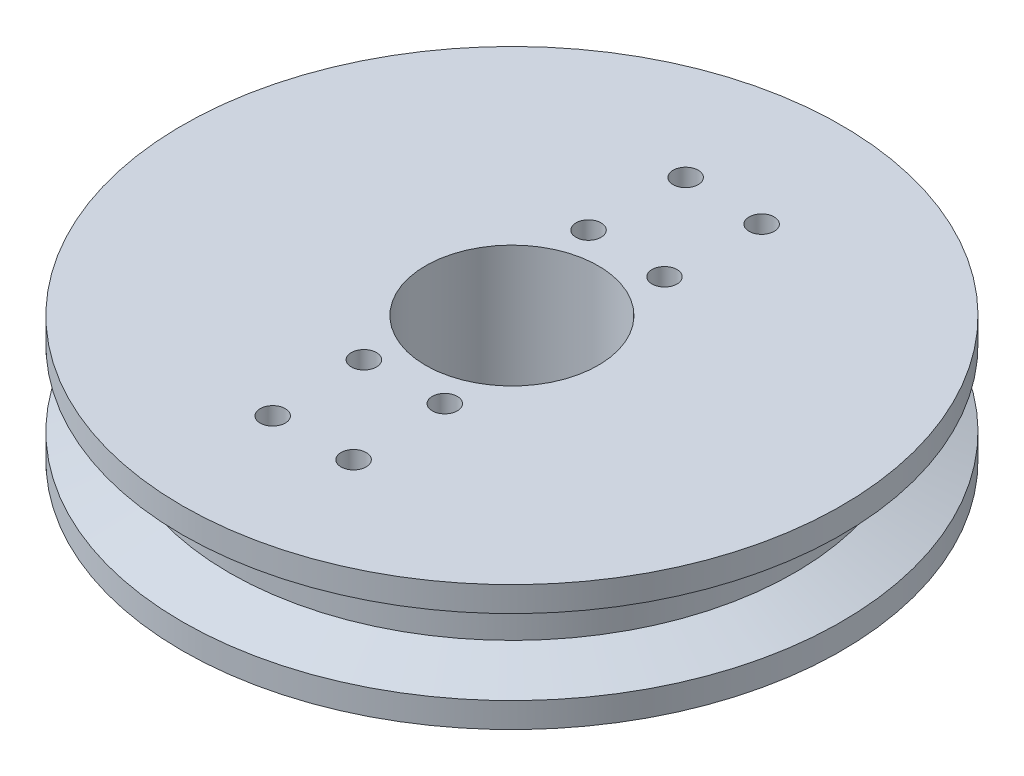
SolidWorks part; units mm, degrees
material "1060 Alloy"
ref_plane "Front Plane" through (0, 0, 0) normal (0, 0, 1) x (1, 0, 0)
ref_plane "Top Plane" through (0, 0, 0) normal (0, 1, 0) x (1, 0, 0)
ref_plane "Right Plane" through (0, 0, 0) normal (1, 0, 0) x (0, 0, -1)
sketch "Sketch1" plane through (0, 0, 0) normal (0, 0, 1) x (1, 0, 0)
  line L0 (0, 0) -> (0, -44.94) construction
  line L1 (27.5, -1.4819) -> (27.5, -41.4819)
  line L7 (105, -1.4819) -> (105, -9.4819)
  line L8 (105, -9.4819) -> (90, -15.4819)
  line L9 (90, -15.4819) -> (90, -27.4819)
  line L11 (90, -27.4819) -> (105, -33.4819)
  line L12 (105, -33.4819) -> (105, -41.4819)
  line L18 (105, -1.4819) -> (27.5, -1.4819)
  line L23 (105, -41.4819) -> (27.5, -41.4819)
  dimension "D2" = 105
  dimension "D3" = 8
  dimension "D4" = 8
  dimension "D5" = 0
  dimension "D6" = 15
  dimension "D7" = 12
  dimension "D8" = 6
  dimension "D9" = 6
revolve "Revolve1" add sketch "Sketch1" angle 360 about L0
sketch "Sketch2" plane through (0, -1.4819, 0) normal (0, 1, 0) x (1, 0, 0)
  line L0 (0, 0) -> (4.5269, -143.7898) construction
  circle A0 centre (-11.3795, -35.7867) radius 4
  circle A1 centre (13.6081, -35) radius 4
  circle A2 centre (14.5526, -65) radius 4
  circle A3 centre (-10.4351, -65.7867) radius 4
  dimension "D1" = 8
  dimension "D2" = 8
  dimension "D3" = 8
  dimension "D4" = 8
  dimension "D5" = 25
  dimension "D6" = 12.5
  dimension "D7" = 12.5
  dimension "D8" = 12.5
  dimension "D9" = 12.5
  dimension "D10" = 30
  dimension "D11" = 30
  dimension "D12" = 65
extrude "Cut-Extrude1" cut sketch "Sketch2" against normal through all
ref_plane "Plane1" through (0, 0, 0) normal (0, 0, 1) x (1, 0, 0)
mirror "Mirror1" about plane through (0, 0, 0) normal (0, 0, 1) of "Cut-Extrude1"
